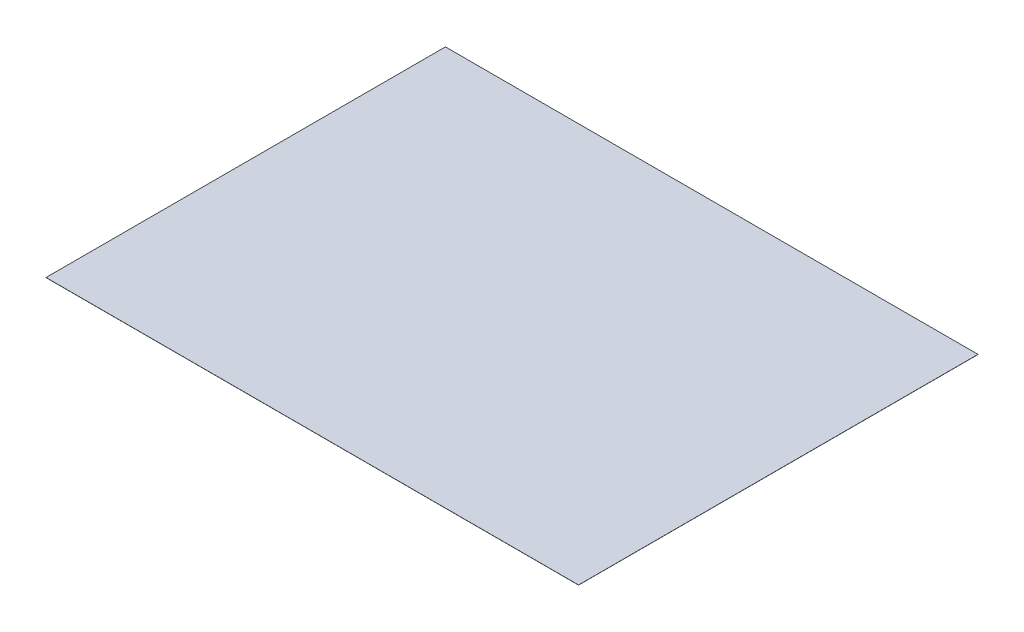
SolidWorks part; units mm, degrees
ref_plane "Front Plane" through (0, 0, 0) normal (0, 0, 1) x (1, 0, 0)
ref_plane "Top Plane" through (0, 0, 0) normal (0, 1, 0) x (1, 0, 0)
ref_plane "Right Plane" through (0, 0, 0) normal (1, 0, 0) x (0, 0, -1)
sketch "Sketch1" plane through (0, 0, 0) normal (0, 1, 0) x (1, 0, 0)
  line L1 (-200, -150) -> (200, -150)
  line L2 (-200, -150) -> (-200, 150)
  line L3 (-200, 150) -> (200, 150)
  line L4 (200, -150) -> (200, 150)
  line L5 (-200, -150) -> (200, 150) construction
  line L6 (-200, 150) -> (200, -150) construction
  point P0 (0, 0)
extrude "Boss-Extrude1" add sketch "Sketch1" along normal blind 0.1
